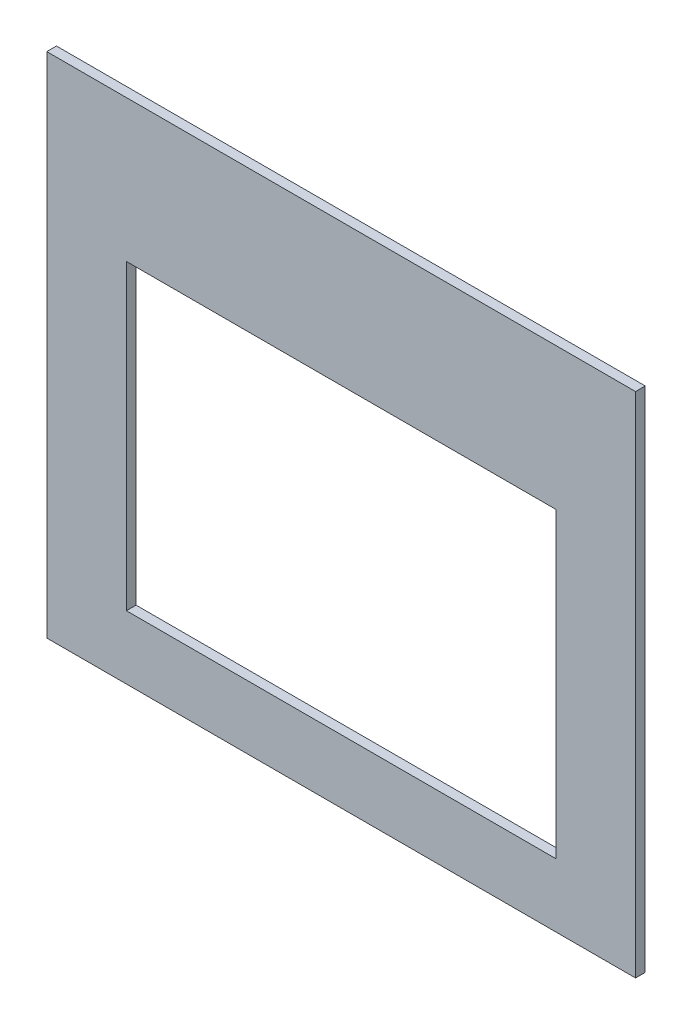
SolidWorks part; units mm, degrees
ref_plane "Front Plane" through (0, 0, 0) normal (0, 0, 1) x (1, 0, 0)
ref_plane "Top Plane" through (0, 0, 0) normal (0, 1, 0) x (1, 0, 0)
ref_plane "Right Plane" through (0, 0, 0) normal (1, 0, 0) x (0, 0, -1)
sketch "Sketch1" plane through (0, 0, 0) normal (0, 0, 1) x (1, 0, 0)
  line L2 (-133, 925.9015) -> (961.2365, 925.9015)
  line L3 (-133, 925.9015) -> (-133, -18)
  line L4 (-133, -18) -> (961.2365, -18)
  line L5 (961.2365, 925.9015) -> (961.2365, -18)
extrude "Boss-Extrude1" add sketch "Sketch1" along normal blind 18
sketch "Sketch2" plane through (0, 0, 18) normal (0, 0, 1) x (1, 0, 0)
  line L0 (961.2365, 662.1515) -> (-133, 662.1515) construction
  line L1 (813.2365, 100) -> (15, 100)
  line L2 (813.2365, 100) -> (813.2365, 662.1515)
  line L3 (813.2365, 662.1515) -> (15, 662.1515)
  line L4 (15, 100) -> (15, 662.1515)
  line L5 (961.2365, 662.1515) -> (-133, 662.1515) construction
  line L6 (813.2365, 100) -> (815.2365, 100) construction
  line L7 (15, 105) -> (15, 141.1) construction
  line L8 (813.2365, 703) -> (813.2365, 100) construction
extrude "Cut-Extrude1" cut sketch "Sketch2" against normal blind 18 contours L2 L1 L4 L3
equation "\"osbthickness\"=18"
equation "\"D1@Boss-Extrude1\"=\"osbthickness\""
